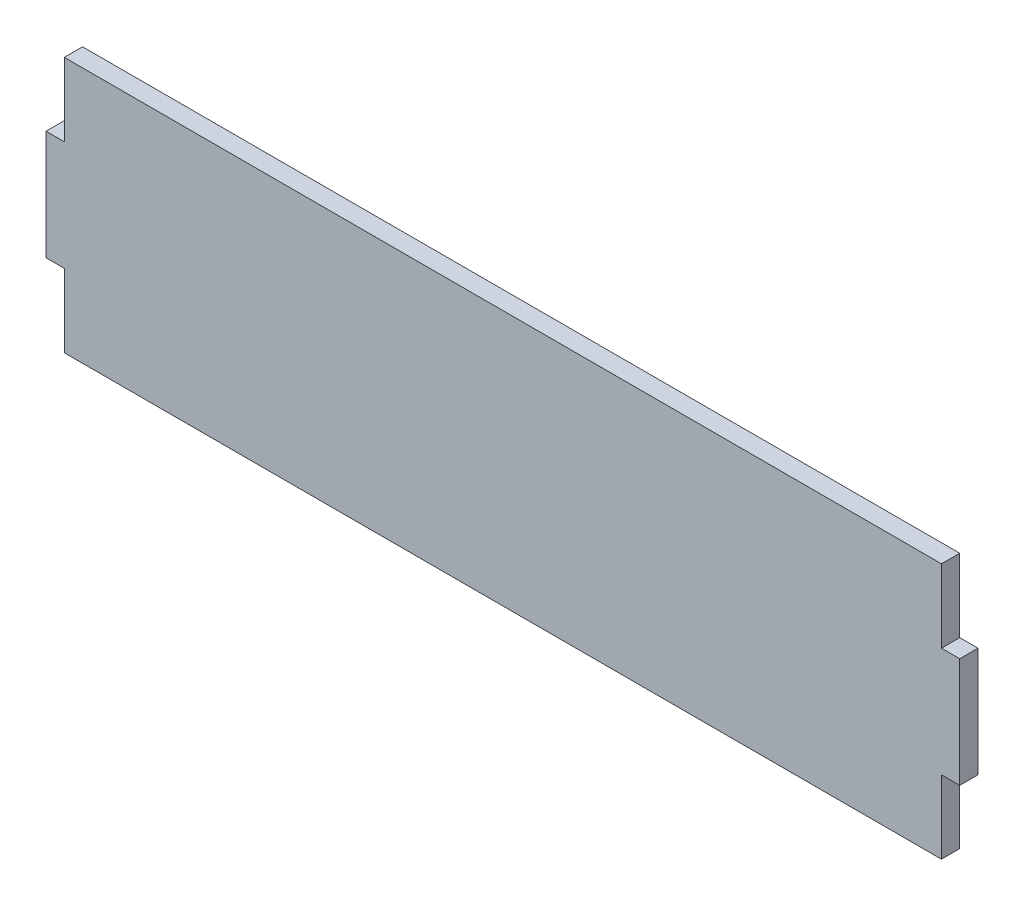
SolidWorks part; units mm, degrees
material "Papier ondulé"
ref_plane "Plan de face" through (0, 0, 0) normal (0, 0, 1) x (1, 0, 0)
ref_plane "Plan de dessus" through (0, 0, 0) normal (0, 1, 0) x (1, 0, 0)
ref_plane "Plan de droite" through (0, 0, 0) normal (1, 0, 0) x (0, 0, -1)
sketch "Esquisse1" plane through (0, 0, 0) normal (0, 0, 1) x (1, 0, 0)
  line L0 (0, 0) -> (240, 0)
  line L1 (240, 0) -> (240, 20)
  line L2 (240, 20) -> (245, 20)
  line L3 (245, 20) -> (245, 50)
  line L4 (245, 50) -> (240, 50)
  line L5 (240, 50) -> (240, 70)
  line L6 (240, 70) -> (0, 70)
  line L7 (0, 70) -> (0, 50)
  line L8 (0, 50) -> (-5, 50)
  line L9 (-5, 50) -> (-5, 20)
  line L10 (-5, 20) -> (0, 20)
  line L11 (0, 20) -> (0, 0)
extrude "Boss.-Extru.1" add sketch "Esquisse1" along normal blind 5
